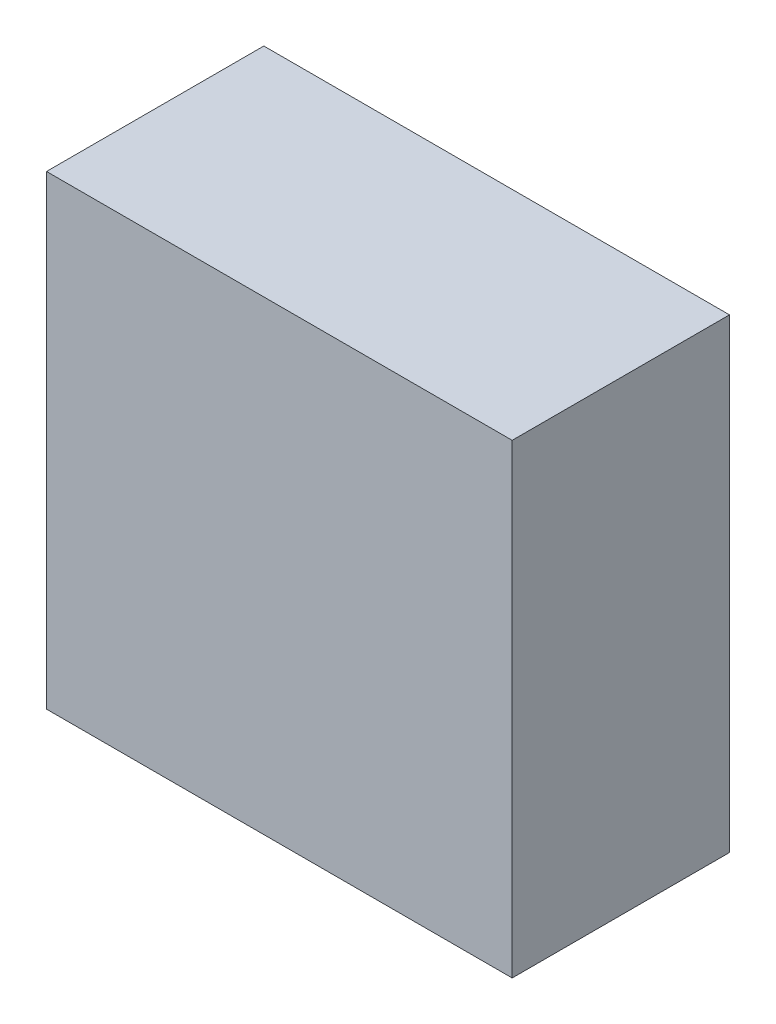
SolidWorks part; units mm, degrees
ref_plane "正面" through (0, 0, 0) normal (0, 0, 1) x (1, 0, 0)
ref_plane "平面" through (0, 0, 0) normal (0, 1, 0) x (1, 0, 0)
ref_plane "右側面" through (0, 0, 0) normal (1, 0, 0) x (0, 0, -1)
sketch "ｽｹｯﾁ1" plane through (0, 0, 0) normal (0, 0, 1) x (1, 0, 0)
  line L1 (0, 0) -> (75, 0)
  line L2 (0, 0) -> (0, 75)
  line L3 (0, 75) -> (75, 75)
  line L4 (75, 0) -> (75, 75)
  dimension "D1" = 75
  dimension "D2" = 75
extrude "ﾎﾞｽ - 押し出し1" add sketch "ｽｹｯﾁ1" along normal blind 35
